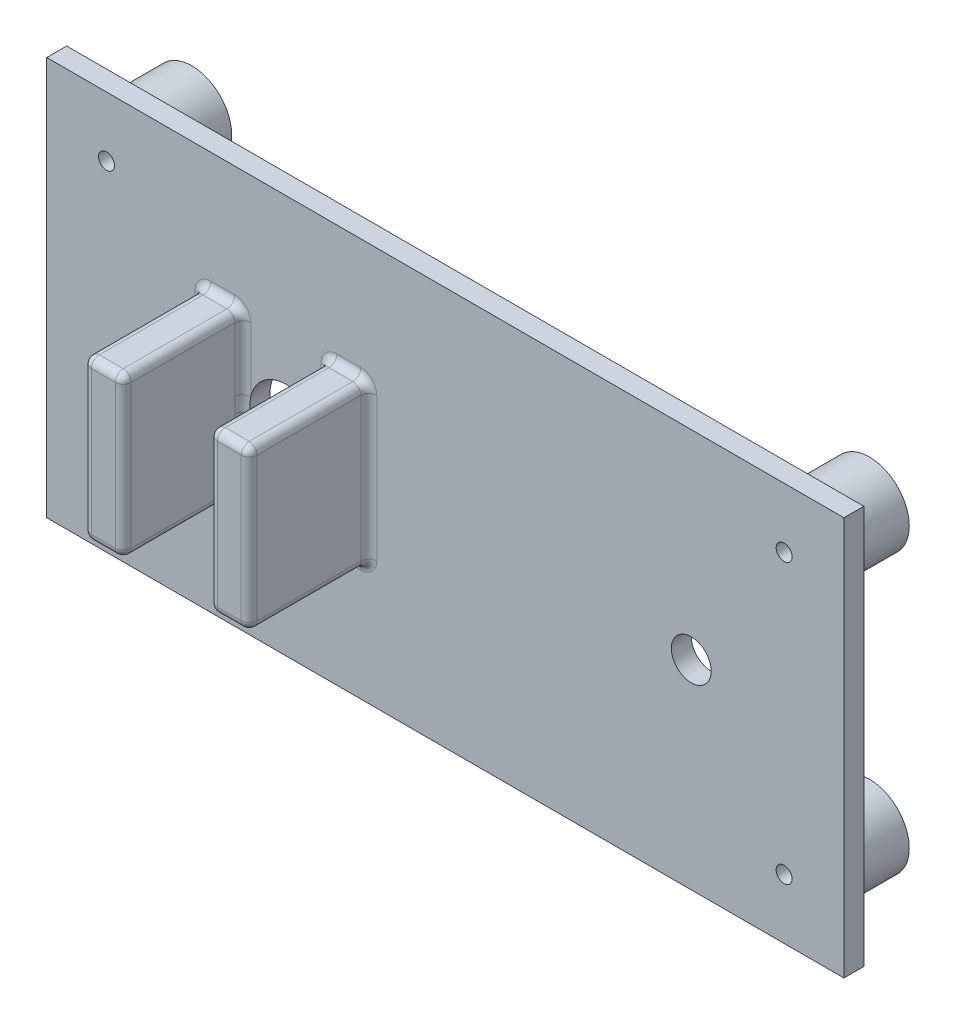
SolidWorks part; units mm, degrees
ref_plane "Front Plane" through (0, 0, 0) normal (0, 0, 1) x (1, 0, 0)
ref_plane "Top Plane" through (0, 0, 0) normal (0, 1, 0) x (1, 0, 0)
ref_plane "Right Plane" through (0, 0, 0) normal (1, 0, 0) x (0, 0, -1)
sketch "Sketch1" plane through (0, 0, 0) normal (0, 0, 1) x (1, 0, 0)
  line L1 (0, 0) -> (100, 0)
  line L2 (0, 0) -> (0, -50)
  line L3 (0, -50) -> (100, -50)
  line L4 (100, 0) -> (100, -50)
  dimension "D1" = 100
  dimension "D2" = 50
extrude "Boss-Extrude1" add sketch "Sketch1" along normal blind 2.5
sketch "Sketch2" plane through (0, 0, 0) normal (0, 0, -1) x (-1, 0, 0)
  line L0 (0, 0) -> (0, -50) construction
  line L1 (-100, 0) -> (0, 0) construction
  line L2 (-50, 0) -> (-50, -50) construction
  line L3 (0, -50) -> (-100, -50) construction
  line L4 (-100, -25) -> (0, -25) construction
  line L5 (-100, -50) -> (-100, 0) construction
  circle A0 centre (-7.5, -7.5) radius 5
  circle A2 centre (-92.5, -7.5) radius 5
  circle A3 centre (-7.5, -42.5) radius 5
  circle A4 centre (-92.5, -42.5) radius 5
  dimension "D1" = 10
  dimension "D2" = 7.5
  dimension "D3" = 7.5
extrude "Boss-Extrude2" add sketch "Sketch2" along normal blind 8.2
sketch "Sketch3" plane through (0, 0, 2.5) normal (0, 0, 1) x (1, 0, 0)
  line L0 (0, 0) -> (0, -50) construction
  line L1 (100, 0) -> (0, 0) construction
  circle A0 centre (30, -25) radius 4.5
  dimension "D1" = 9
  dimension "D2" = 30
  dimension "D3" = 25
extrude "Cut-Extrude1" cut sketch "Sketch3" against normal through all both and the other way through all
sketch "Sketch4" plane through (0, 0, -8.2) normal (0, 0, -1) x (-1, 0, 0)
  circle A0 centre (-92.5, -7.5) radius 1
  circle A1 centre (-92.5, -42.5) radius 1
  circle A2 centre (-7.5, -42.5) radius 1
  circle A3 centre (-7.5, -7.5) radius 1
  dimension "D1" = 2
  dimension "D2" = 2
  dimension "D3" = 2
  dimension "D4" = 2
extrude "Cut-Extrude4" cut sketch "Sketch4" against normal through all both and the other way through all
sketch "Sketch6" plane through (0, 0, 2.5) normal (0, 0, 1) x (1, 0, 0)
  line L0 (0, 0) -> (0, -50) construction
  line L1 (24.6, -15) -> (19.6, -15)
  line L2 (24.6, -15) -> (24.6, -35)
  line L3 (24.6, -35) -> (19.6, -35)
  line L4 (19.6, -15) -> (19.6, -35)
  line L5 (100, 0) -> (0, 0) construction
  line L7 (30, 0) -> (30, -50) construction
  line L8 (40.4, -15) -> (40.4, -35)
  line L9 (35.4, -35) -> (40.4, -35)
  line L10 (35.4, -15) -> (35.4, -35)
  line L11 (35.4, -15) -> (40.4, -15)
  circle A0 centre (30, -25) radius 4.5 construction
  dimension "D1" = 24.6
  dimension "D2" = 5
  dimension "D3" = 15
  dimension "D4" = 20
  dimension "D5" = 0
extrude "Boss-Extrude3" add sketch "Sketch6" along normal blind 15
fillet "Fillet1" radius 1 24 edges at (37.9, -35, 17.5) (37.9, -35, 2.5) (40.4, -35, 10) (40.4, -25, 17.5) (40.4, -25, 2.5) (35.4, -25, 17.5) (35.4, -35, 10) (35.4, -25, 2.5) (40.4, -15, 10) (37.9, -15, 17.5) (35.4, -15, 10) (37.9, -15, 2.5) (22.1, -15, 17.5) (22.1, -15, 2.5) (24.6, -25, 17.5) (24.6, -15, 10) (24.6, -25, 2.5) (22.1, -35, 17.5) (24.6, -35, 10) (22.1, -35, 2.5) (19.6, -15, 10) (19.6, -25, 17.5) (19.6, -35, 10) (19.6, -25, 2.5)
sketch "Sketch7" plane through (0, 0, 2.5) normal (0, 0, 1) x (1, 0, 0)
  line L0 (100, 0) -> (0, 0) construction
  circle A0 centre (80.8575, -25) radius 2.5
  dimension "D2" = 5
  dimension "D1" = 25
extrude "Cut-Extrude5" cut sketch "Sketch7" against normal through all both and the other way through all
